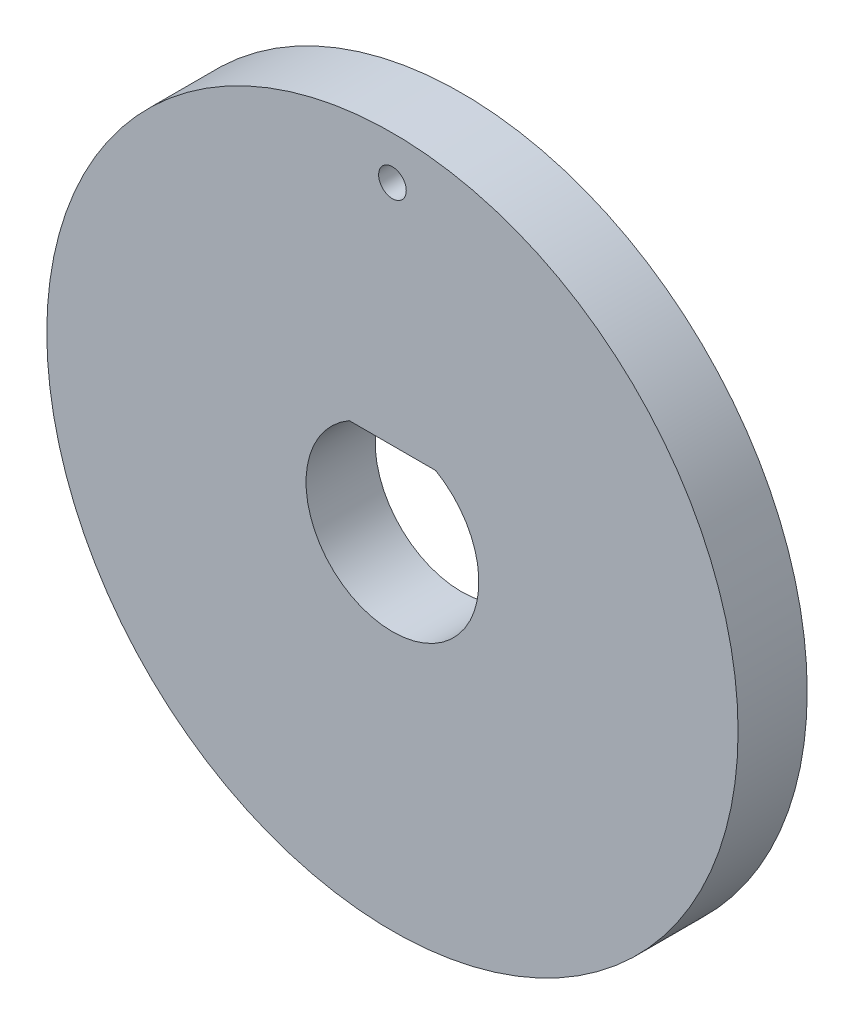
SolidWorks part; units mm, degrees
ref_plane "Front Plane" through (0, 0, 0) normal (0, 0, 1) x (1, 0, 0)
ref_plane "Top Plane" through (0, 0, 0) normal (0, 1, 0) x (1, 0, 0)
ref_plane "Right Plane" through (0, 0, 0) normal (1, 0, 0) x (0, 0, -1)
sketch "Sketch2" plane through (0, 0, 0) normal (0, 0, 1) x (1, 0, 0)
  line L0 (-1.5875, 2.7496) -> (1.5875, 2.7496)
  line L1 (0, 9.525) -> (0, 12.7) construction
  arc A0 (-1.5875, 2.7496) -> (1.5875, 2.7496) centre (0, 0) ccw
  circle A1 centre (0, 0) radius 12.7
  circle A2 centre (0, 0) radius 9.525 construction
  circle A3 centre (0, 11.1125) radius 0.508
  dimension "D1" = 6.35
  dimension "D2" = 25.4
  dimension "D4" = 19.05
  dimension "D5" = 1.016
  dimension "D3" = 3.175
extrude "Boss-Extrude1" add sketch "Sketch2" along normal blind 2.54
